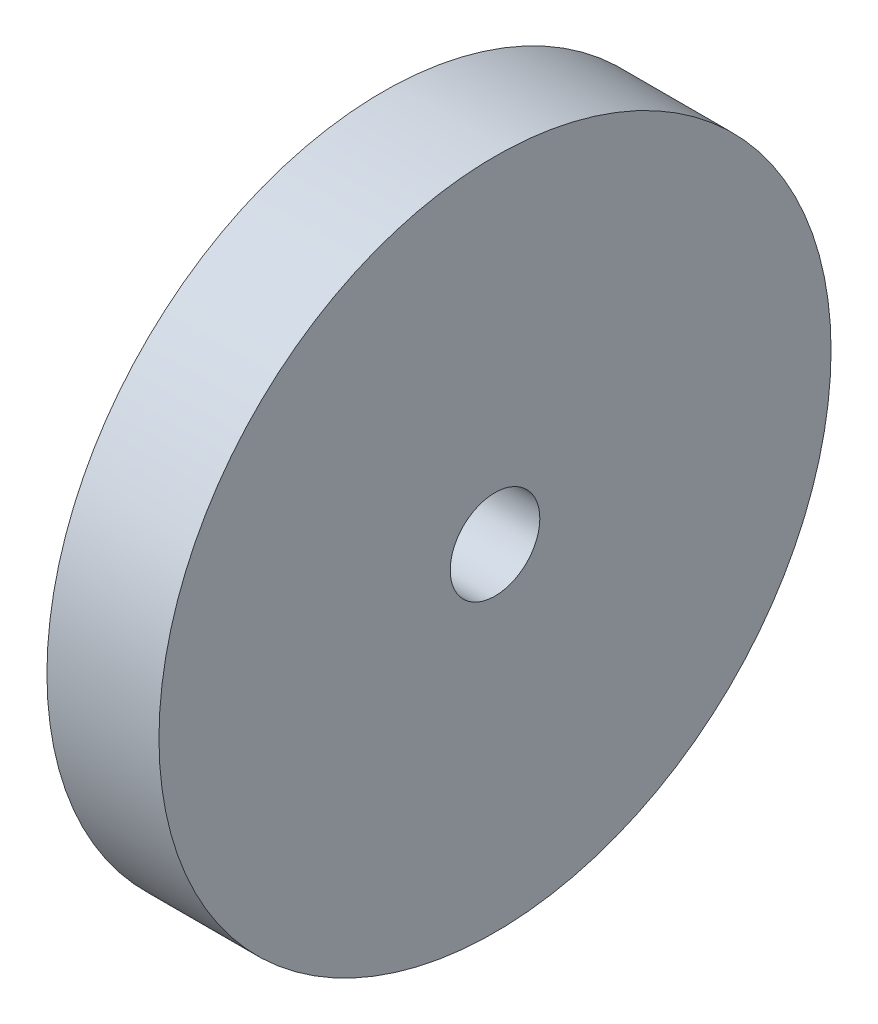
SolidWorks part; units mm, degrees
ref_plane "Alzado" through (0, 0, 0) normal (0, 0, 1) x (1, 0, 0)
ref_plane "Planta" through (0, 0, 0) normal (0, 1, 0) x (1, 0, 0)
ref_plane "Vista lateral" through (0, 0, 0) normal (1, 0, 0) x (0, 0, -1)
sketch "Croquis1" plane through (0, 0, 0) normal (1, 0, 0) x (0, 0, -1)
  circle A0 centre (0, 0) radius 15
  circle A1 centre (0, 0) radius 2
  dimension "D1" = 4
  dimension "D2" = 30
extrude "Saliente-Extruir1" add sketch "Croquis1" along normal blind 5
